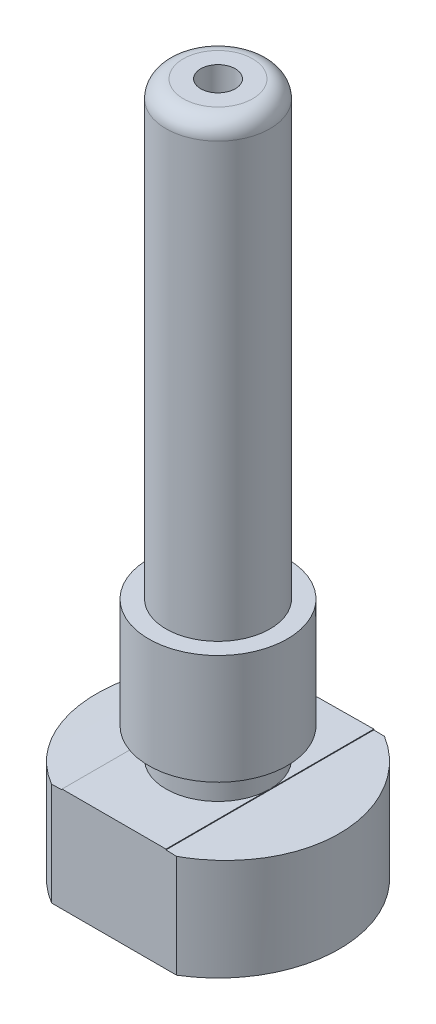
SolidWorks part; units mm, degrees
material "AISI Type A2 Tool Steel"
ref_plane "Front Plane" through (0, 0, 0) normal (0, 0, 1) x (1, 0, 0)
ref_plane "Top Plane" through (0, 0, 0) normal (0, 1, 0) x (1, 0, 0)
ref_plane "Right Plane" through (0, 0, 0) normal (1, 0, 0) x (0, 0, -1)
sketch "Sketch1" plane through (0, 0, 0) normal (0, 0, 1) x (1, 0, 0)
  line L0 (0, 0) -> (-3.5, 0)
  line L1 (-3.5, 0) -> (-3.5, 3)
  line L2 (-3.5, 3) -> (-1.5, 3)
  line L3 (-1.5, 3) -> (-1.5, 3.8332)
  line L4 (-1, 20) -> (0, 20)
  line L5 (0, 7) -> (0, 25.6531) construction
  line L6 (-1.5, 7) -> (-2, 7)
  line L7 (-1.5, 3.8332) -> (-2, 3.8332)
  line L8 (-2, 7) -> (-2, 3.8332)
  line L9 (-1.5, 7) -> (-1.5, 19.5)
  line L10 (0, 0) -> (0, 20)
  arc A0 (-1, 20) -> (-1.5, 19.5) centre (-1, 19.5) ccw
  dimension "D1" = 0.5
revolve "Revolve2" add sketch "Sketch1" angle 360 about L5
ref_plane "Plane1" through (0, 20, 0) normal (0, 1, 0) x (1, 0, 0)
sketch "Sketch2" plane through (0, 20, 0) normal (0, 1, 0) x (1, 0, 0)
  circle A0 centre (0, 0) radius 0.5
extrude "Cut-Extrude2" cut sketch "Sketch2" against normal through all
hole_wizard "Ø2.0mm Dowel Hole1" positions "Sketch5" profile "Sketch4" hole size "Ø2.0" standard "GB"
sketch "Sketch5" plane through (0, 0, 0) normal (0, -1, 0) x (-1, 0, 0)
  point P0 (0, 0)
sketch "Sketch4" plane through (0, 0, 0) normal (1, 0, 0) x (0, 0, -1)
  line L0 (0, 0) -> (0, 2.6009)
  line L1 (0, 2.6009) -> (1, 2)
  line L2 (1, 2) -> (1, 0)
  line L5 (1, 0) -> (0, 0)
  line L10 (0, 2.6009) -> (-1, 2) construction
  line L11 (0, -6.35) -> (0, 107.95) construction
  dimension "Hole Dia." = 2
  dimension "Hole Depth" = 2
  dimension "Drill Angle" = 118
sketch "Sketch6" plane through (0, 20, 0) normal (0, 1, 0) x (1, 0, 0)
  line L0 (1.8028, -3) -> (-1.8028, -3)
  line L1 (-1.8618, 2.9638) -> (1.8028, 3)
  circle A0 centre (0, 0) radius 3.5 construction
  arc A1 (-1.8618, 2.9638) -> (1.8028, 3) centre (0, 0) cw
  arc A2 (-1.8028, -3) -> (1.8028, -3) centre (0, 0) ccw
extrude "Cut-Extrude3" cut sketch "Sketch6" against normal through all
sketch "Sketch7" plane through (0, 0, 0) normal (0, 0, 1) x (1, 0, 0)
  line L0 (-4.1561, 2.8389) -> (-4.1561, 3.2395)
  line L1 (-1.5, 3.2395) -> (-1.5, 2.979)
  line L2 (-4.1561, 3.2395) -> (-1.5, 3.2395)
  line L3 (-1.5, 3.8332) -> (-1.5, 3) construction
  line L7 (4.1561, 3.2395) -> (1.5, 3.2395)
  line L8 (1.5, 3.2395) -> (1.5, 2.979)
  line L9 (4.1561, 2.8389) -> (4.1561, 3.2395)
  arc A0 (1.5, 2.979) -> (4.1561, 2.8389) centre (0, -50.7) cw
  arc A1 (-1.5, 2.979) -> (-4.1561, 2.8389) centre (0, -50.7) ccw
extrude "Cut-Extrude4" cut sketch "Sketch7" along normal blind 5 and the other way blind 18
scale "Scale1" scale about centroid uniform scaling yes scale factor 1.2
